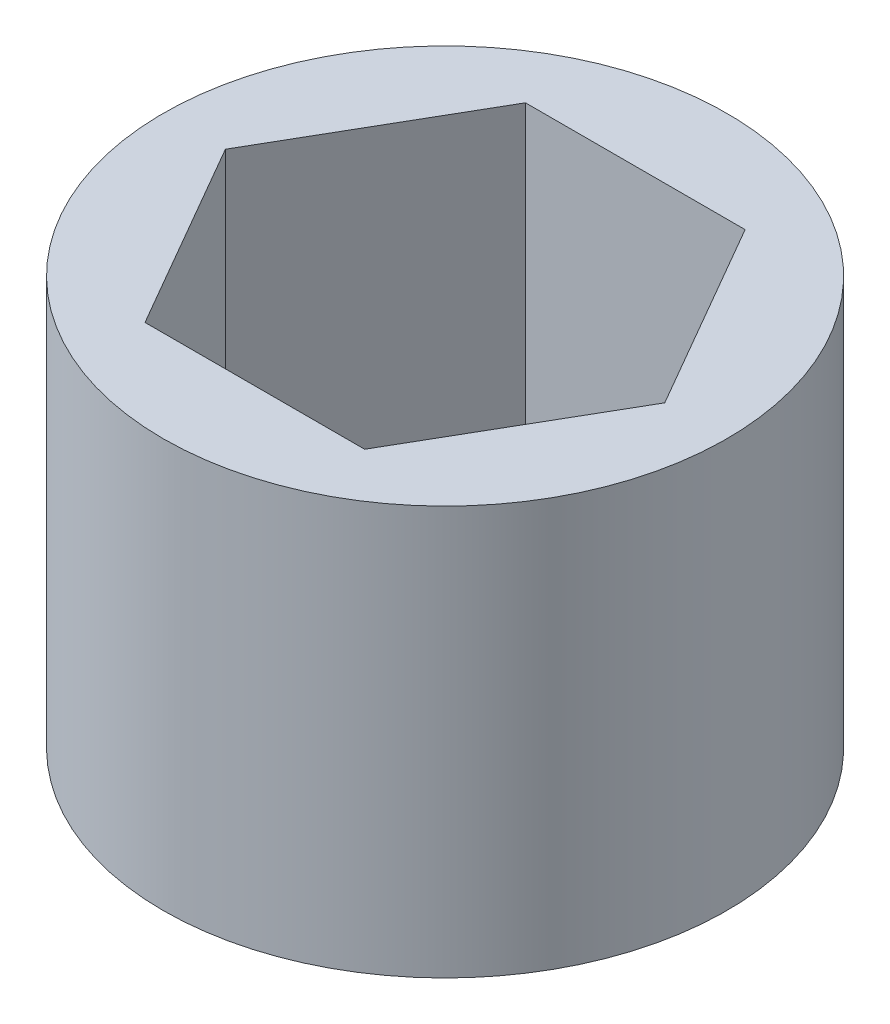
SolidWorks part; units mm, degrees
ref_plane "Front Plane" through (0, 0, 0) normal (0, 0, 1) x (1, 0, 0)
ref_plane "Top Plane" through (0, 0, 0) normal (0, 1, 0) x (1, 0, 0)
ref_plane "Right Plane" through (0, 0, 0) normal (1, 0, 0) x (0, 0, -1)
sketch "Sketch1" plane through (0, 0, 0) normal (0, 1, 0) x (1, 0, 0)
  line L1 (7.9189, 0) -> (3.9595, 6.858)
  line L2 (3.9595, 6.858) -> (-3.9595, 6.858)
  line L3 (-3.9595, 6.858) -> (-7.9189, 0)
  line L4 (-7.9189, 0) -> (-3.9595, -6.858)
  line L5 (-3.9595, -6.858) -> (3.9595, -6.858)
  line L6 (3.9595, -6.858) -> (7.9189, 0)
  circle A0 centre (0, 0) radius 6.858 construction
  circle A1 centre (0, 0) radius 10.16
  dimension "D2" = 20.32
  dimension "D1" = 13.716
extrude "Boss-Extrude1" add sketch "Sketch1" along normal blind 14.732
